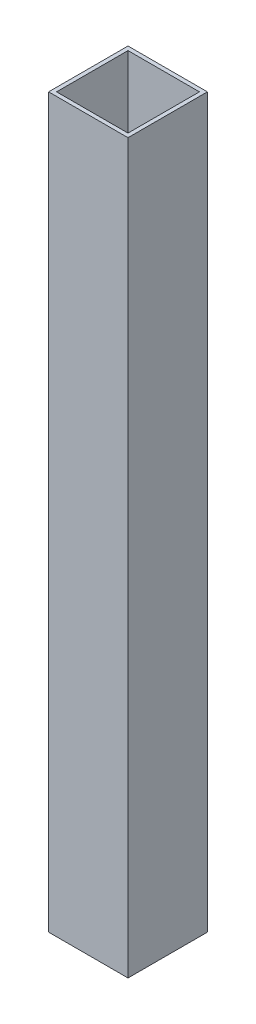
SolidWorks part; units mm, degrees
ref_plane "Front Plane" through (0, 0, 0) normal (0, 0, 1) x (1, 0, 0)
ref_plane "Top Plane" through (0, 0, 0) normal (0, 1, 0) x (1, 0, 0)
ref_plane "Right Plane" through (0, 0, 0) normal (1, 0, 0) x (0, 0, -1)
sketch "Sketch1" plane through (0, 0, 0) normal (0, 1, 0) x (1, 0, 0)
  line L1 (0, 0) -> (30, 0)
  line L2 (0, 0) -> (0, -30)
  line L3 (0, -30) -> (30, -30)
  line L4 (30, 0) -> (30, -30)
  line L5 (1.5, -1.5) -> (28.5, -1.5)
  line L6 (1.5, -1.5) -> (1.5, -28.5)
  line L7 (1.5, -28.5) -> (28.5, -28.5)
  line L8 (28.5, -1.5) -> (28.5, -28.5)
  dimension "D1" = 30
  dimension "D2" = 30
  dimension "D3" = 1.5
  dimension "D4" = 1.5
  dimension "D5" = 1.5
  dimension "D6" = 1.5
extrude "Boss-Extrude1" add sketch "Sketch1" along normal blind 275
